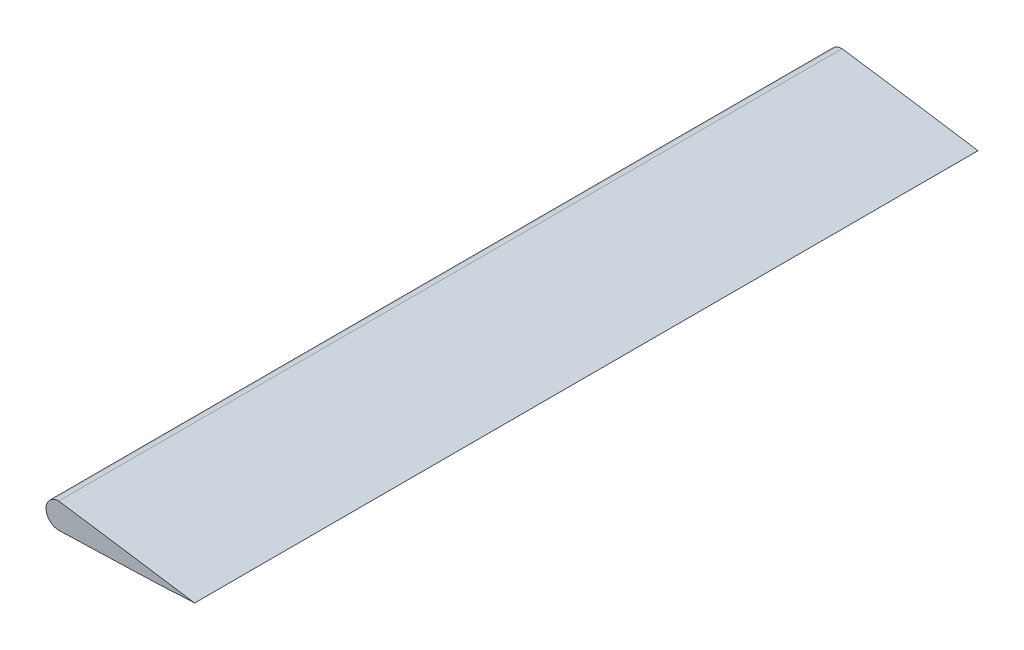
SolidWorks part; units mm, degrees
ref_plane "Front Plane" through (0, 0, 0) normal (0, 0, 1) x (1, 0, 0)
ref_plane "Top Plane" through (0, 0, 0) normal (0, 1, 0) x (1, 0, 0)
ref_plane "Right Plane" through (0, 0, 0) normal (1, 0, 0) x (0, 0, -1)
curve "Curve1"
  spline degree 3 poles (113.1638, 0.0058, 0) (114.2125, -0.0111, 0) (113.1709, 0.0811, 0) (112.3431, 0.2203, 0) (110.3841, 0.5215, 0) (108.0345, 0.92, 0) (105.0184, 1.3962, 0) (101.4945, 1.9271, 0) (97.463, 2.5292, 0) (92.9941, 3.1955, 0) (88.1458, 3.9135, 0) (82.9876, 4.6742, 0) (77.589, 5.4565, 0) (72.0235, 6.2448, 0) (66.366, 7.016, 0) (60.6906, 7.741, 0) (55.0652, 8.3861, 0) (49.541, 8.8971, 0) (44.1567, 9.2392, 0) (38.9435, 9.3951, 0) (33.9297, 9.3575, 0) (29.1403, 9.1242, 0) (24.602, 8.7097, 0) (20.3453, 8.1494, 0) (16.4081, 7.4675, 0) (12.8301, 6.6821, 0) (9.645, 5.8131, 0) (6.8837, 4.8794, 0) (4.5637, 3.9037, 0) (2.7157, 2.9132, 0) (1.3101, 1.9311, 0) (0.4517, 1.0168, 0) (-0.14, 0.1424, 0) (0.2858, -0.7724, 0) (1.3884, -1.2024, 0) (2.9179, -1.7091, 0) (5.0763, -2.0733, 0) (7.7801, -2.3806, 0) (11.0432, -2.5933, 0) (14.8282, -2.7301, 0) (19.104, -2.7893, 0) (23.8262, -2.784, 0) (28.9449, -2.7227, 0) (34.404, -2.6158, 0) (40.1412, -2.4729, 0) (46.0896, -2.3047, 0) (52.179, -2.1196, 0) (58.3361, -1.9262, 0) (64.4871, -1.7291, 0) (70.5576, -1.5345, 0) (76.4738, -1.3473, 0) (82.1636, -1.1689, 0) (87.5572, -1.002, 0) (92.5888, -0.8484, 0) (97.1946, -0.7053, 0) (101.3214, -0.5753, 0) (104.9082, -0.4471, 0) (107.9665, -0.3053, 0) (110.3459, -0.1514, 0) (112.3264, -0.0523, 0) (113.1638, 0.0058, 0) (114.2125, -0.0111, 0) (113.1709, 0.0811, 0) knots -0.014699 -0.006722 -0.001718 0 0.001709 0.006706 0.014679 0.02532 0.038434 0.053918 0.071593 0.091201 0.11246 0.135079 0.158745 0.183125 0.207894 0.232709 0.25724 0.281239 0.304568 0.327118 0.348787 0.369502 0.389214 0.407805 0.425104 0.44096 0.455242 0.467848 0.478705 0.487774 0.495056 0.50059 0.504447 0.507433 0.512166 0.519163 0.528543 0.540328 0.554465 0.570868 0.589394 0.609852 0.632039 0.655706 0.680582 0.706382 0.732793 0.759501 0.78618 0.812514 0.838179 0.862858 0.886256 0.908083 0.928063 0.945961 0.961531 0.974665 0.985301 0.993278 0.998282 1 1.001709 1.006706 1.014679 periodic
sketch "Sketch1" plane through (0, 0, 0) normal (0, 0, 1) x (1, 0, 0)
  line L0 (0, 0) -> (0.0049, 0) construction
  arc A0 (80, 5.1064) -> (80, -1.2369) centre (80, 1.9348) ccw
  spline S0 degree 3 poles (113.1638, 0.0058) (114.2125, -0.0111) (113.1709, 0.0811) (112.3431, 0.2203) (110.3841, 0.5215) (108.0345, 0.92) (105.0184, 1.3962) (101.4945, 1.9271) (97.463, 2.5292) (92.9941, 3.1955) (88.1458, 3.9135) (82.9876, 4.6742) (77.589, 5.4565) (72.0235, 6.2448) (66.366, 7.016) (60.6906, 7.741) (55.0652, 8.3861) (49.541, 8.8971) (44.1567, 9.2392) (38.9435, 9.3951) (33.9297, 9.3575) (29.1403, 9.1242) (24.602, 8.7097) (20.3453, 8.1494) (16.4081, 7.4675) (12.8301, 6.6821) (9.645, 5.8131) (6.8837, 4.8794) (4.5637, 3.9037) (2.7157, 2.9132) (1.3101, 1.9311) (0.4517, 1.0168) (-0.14, 0.1424) (0.2858, -0.7724) (1.3884, -1.2024) (2.9179, -1.7091) (5.0763, -2.0733) (7.7801, -2.3806) (11.0432, -2.5933) (14.8282, -2.7301) (19.104, -2.7893) (23.8262, -2.784) (28.9449, -2.7227) (34.404, -2.6158) (40.1412, -2.4729) (46.0896, -2.3047) (52.179, -2.1196) (58.3361, -1.9262) (64.4871, -1.7291) (70.5576, -1.5345) (76.4738, -1.3473) (82.1636, -1.1689) (87.5572, -1.002) (92.5888, -0.8484) (97.1946, -0.7053) (101.3214, -0.5753) (104.9082, -0.4471) (107.9665, -0.3053) (110.3459, -0.1514) (112.3264, -0.0523) (113.1638, 0.0058) (114.2125, -0.0111) (113.1709, 0.0811) knots -0.014699 -0.006722 -0.001718 0 0.001709 0.006706 0.014679 0.02532 0.038434 0.053918 0.071593 0.091201 0.11246 0.135079 0.158745 0.183125 0.207894 0.232709 0.25724 0.281239 0.304568 0.327118 0.348787 0.369502 0.389214 0.407805 0.425104 0.44096 0.455242 0.467848 0.478705 0.487774 0.495056 0.50059 0.504447 0.507433 0.512166 0.519163 0.528543 0.540328 0.554465 0.570868 0.589394 0.609852 0.632039 0.655706 0.680582 0.706382 0.732793 0.759501 0.78618 0.812514 0.838179 0.862858 0.886256 0.908083 0.928063 0.945961 0.961531 0.974665 0.985301 0.993278 0.998282 1 1.001709 1.006706 1.014679 only from (114, 0) to (114, 0) construction
  spline S1 degree 3 poles (80, -1.2369) (80.7541, -1.2133) (83.3136, -1.1333) (87.5572, -1.002) (92.5888, -0.8484) (97.1946, -0.7053) (101.3214, -0.5753) (104.9082, -0.4471) (107.9665, -0.3053) (110.3459, -0.1514) (112.3264, -0.0523) (113.1638, 0.0058) (114.2125, -0.0111) (113.1709, 0.0811) (112.3431, 0.2203) (110.3841, 0.5215) (108.0345, 0.92) (105.0184, 1.3962) (101.4945, 1.9271) (97.463, 2.5292) (92.9941, 3.1955) (88.1458, 3.9135) (83.7728, 4.5584) (81.0225, 4.9585) (80, 5.1064) knots 0.853084 0.853084 0.853084 0.853084 0.862858 0.886256 0.908083 0.928063 0.945961 0.961531 0.974665 0.985301 0.993278 0.998282 1 1.001709 1.006706 1.014679 1.02532 1.038434 1.053918 1.071593 1.091201 1.11246 1.135079 1.148463 1.148463 1.148463 1.148463
  point P1 (0, 0)
extrude "Boss-Extrude1" add sketch "Sketch1" along normal blind 196
